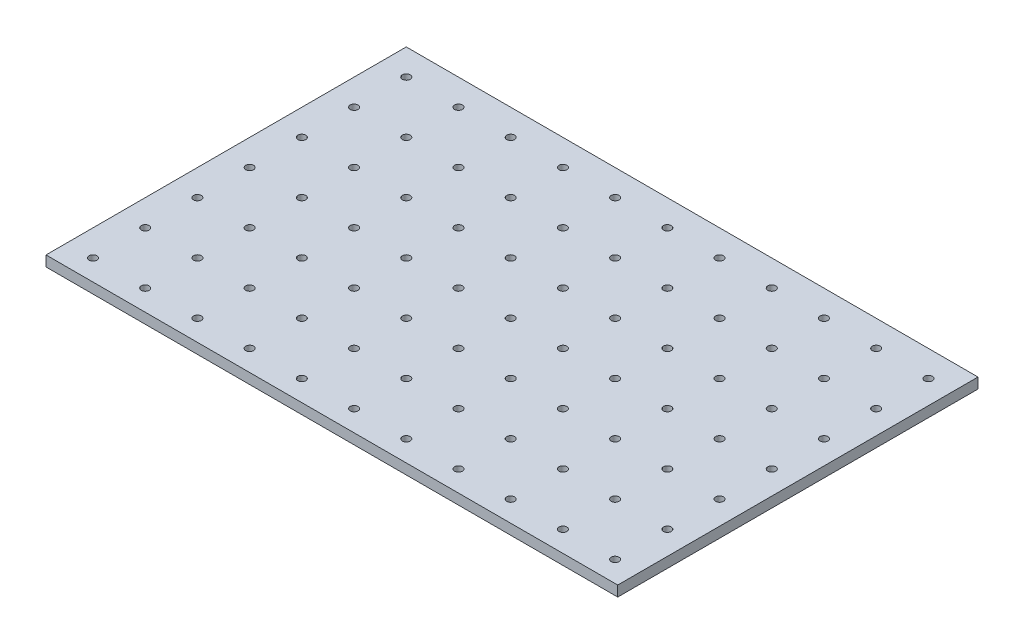
SolidWorks part; units mm, degrees
ref_plane "Front Plane" through (0, 0, 0) normal (0, 0, 1) x (1, 0, 0)
ref_plane "Top Plane" through (0, 0, 0) normal (0, 1, 0) x (1, 0, 0)
ref_plane "Right Plane" through (0, 0, 0) normal (1, 0, 0) x (0, 0, -1)
sketch "Sketch1" plane through (0, 0, 0) normal (0, 1, 0) x (1, 0, 0)
  line L1 (-61.9653, 45.6647) -> (157.0347, 45.6647)
  line L2 (-61.9653, 45.6647) -> (-61.9653, -92.3353)
  line L3 (-61.9653, -92.3353) -> (157.0347, -92.3353)
  line L4 (157.0347, 45.6647) -> (157.0347, -92.3353)
  dimension "D1" = 138
  dimension "D2" = 219
extrude "Boss-Extrude1" add sketch "Sketch1" along normal blind 4
sketch "Sketch2" plane through (0, 4, 0) normal (0, 1, 0) x (1, 0, 0)
  line L1 (157.0347, 45.6647) -> (-61.9653, 45.6647) construction
  line L2 (-61.9653, 45.6647) -> (-61.9653, -92.3353) construction
  circle A77 centre (-51.9653, 35.6647) radius 1.5
  circle A78 centre (-31.9653, 35.6647) radius 1.5
  circle A79 centre (-11.9653, 35.6647) radius 1.5
  circle A80 centre (8.0347, 35.6647) radius 1.5
  circle A81 centre (28.0347, 35.6647) radius 1.5
  circle A82 centre (48.0347, 35.6647) radius 1.5
  circle A83 centre (68.0347, 35.6647) radius 1.5
  circle A84 centre (88.0347, 35.6647) radius 1.5
  circle A85 centre (108.0347, 35.6647) radius 1.5
  circle A86 centre (128.0347, 35.6647) radius 1.5
  circle A87 centre (148.0347, 35.6647) radius 1.5
  circle A88 centre (-31.9653, 15.6647) radius 1.5
  circle A89 centre (-11.9653, 15.6647) radius 1.5
  circle A90 centre (8.0347, 15.6647) radius 1.5
  circle A91 centre (28.0347, 15.6647) radius 1.5
  circle A92 centre (48.0347, 15.6647) radius 1.5
  circle A93 centre (68.0347, 15.6647) radius 1.5
  circle A94 centre (88.0347, 15.6647) radius 1.5
  circle A95 centre (108.0347, 15.6647) radius 1.5
  circle A96 centre (128.0347, 15.6647) radius 1.5
  circle A97 centre (148.0347, 15.6647) radius 1.5
  circle A98 centre (-31.9653, -4.3353) radius 1.5
  circle A99 centre (-11.9653, -4.3353) radius 1.5
  circle A100 centre (8.0347, -4.3353) radius 1.5
  circle A101 centre (28.0347, -4.3353) radius 1.5
  circle A102 centre (48.0347, -4.3353) radius 1.5
  circle A103 centre (68.0347, -4.3353) radius 1.5
  circle A104 centre (88.0347, -4.3353) radius 1.5
  circle A105 centre (108.0347, -4.3353) radius 1.5
  circle A106 centre (128.0347, -4.3353) radius 1.5
  circle A107 centre (148.0347, -4.3353) radius 1.5
  circle A108 centre (-31.9653, -24.3353) radius 1.5
  circle A109 centre (-11.9653, -24.3353) radius 1.5
  circle A110 centre (8.0347, -24.3353) radius 1.5
  circle A111 centre (28.0347, -24.3353) radius 1.5
  circle A112 centre (48.0347, -24.3353) radius 1.5
  circle A113 centre (68.0347, -24.3353) radius 1.5
  circle A114 centre (88.0347, -24.3353) radius 1.5
  circle A115 centre (108.0347, -24.3353) radius 1.5
  circle A116 centre (128.0347, -24.3353) radius 1.5
  circle A117 centre (148.0347, -24.3353) radius 1.5
  circle A118 centre (-31.9653, -44.3353) radius 1.5
  circle A119 centre (-11.9653, -44.3353) radius 1.5
  circle A120 centre (8.0347, -44.3353) radius 1.5
  circle A121 centre (28.0347, -44.3353) radius 1.5
  circle A122 centre (48.0347, -44.3353) radius 1.5
  circle A123 centre (68.0347, -44.3353) radius 1.5
  circle A124 centre (88.0347, -44.3353) radius 1.5
  circle A125 centre (108.0347, -44.3353) radius 1.5
  circle A126 centre (128.0347, -44.3353) radius 1.5
  circle A127 centre (148.0347, -44.3353) radius 1.5
  circle A128 centre (-31.9653, -64.3353) radius 1.5
  circle A129 centre (-11.9653, -64.3353) radius 1.5
  circle A130 centre (8.0347, -64.3353) radius 1.5
  circle A131 centre (28.0347, -64.3353) radius 1.5
  circle A132 centre (48.0347, -64.3353) radius 1.5
  circle A133 centre (68.0347, -64.3353) radius 1.5
  circle A134 centre (88.0347, -64.3353) radius 1.5
  circle A135 centre (108.0347, -64.3353) radius 1.5
  circle A136 centre (128.0347, -64.3353) radius 1.5
  circle A137 centre (148.0347, -64.3353) radius 1.5
  circle A138 centre (-31.9653, -84.3353) radius 1.5
  circle A139 centre (-11.9653, -84.3353) radius 1.5
  circle A140 centre (8.0347, -84.3353) radius 1.5
  circle A141 centre (28.0347, -84.3353) radius 1.5
  circle A142 centre (48.0347, -84.3353) radius 1.5
  circle A143 centre (68.0347, -84.3353) radius 1.5
  circle A144 centre (88.0347, -84.3353) radius 1.5
  circle A145 centre (108.0347, -84.3353) radius 1.5
  circle A146 centre (128.0347, -84.3353) radius 1.5
  circle A147 centre (148.0347, -84.3353) radius 1.5
  circle A148 centre (-51.9653, 15.6647) radius 1.5
  circle A149 centre (-51.9653, -4.3353) radius 1.5
  circle A150 centre (-51.9653, -24.3353) radius 1.5
  circle A151 centre (-51.9653, -44.3353) radius 1.5
  circle A152 centre (-51.9653, -64.3353) radius 1.5
  circle A153 centre (-51.9653, -84.3353) radius 1.5
  dimension "D1" = 10
  dimension "D2" = 10
  dimension "D5" = 3
  dimension "D4" = 11
  dimension "D3" = 7
extrude "Cut-Extrude1" cut sketch "Sketch2" against normal blind 5
